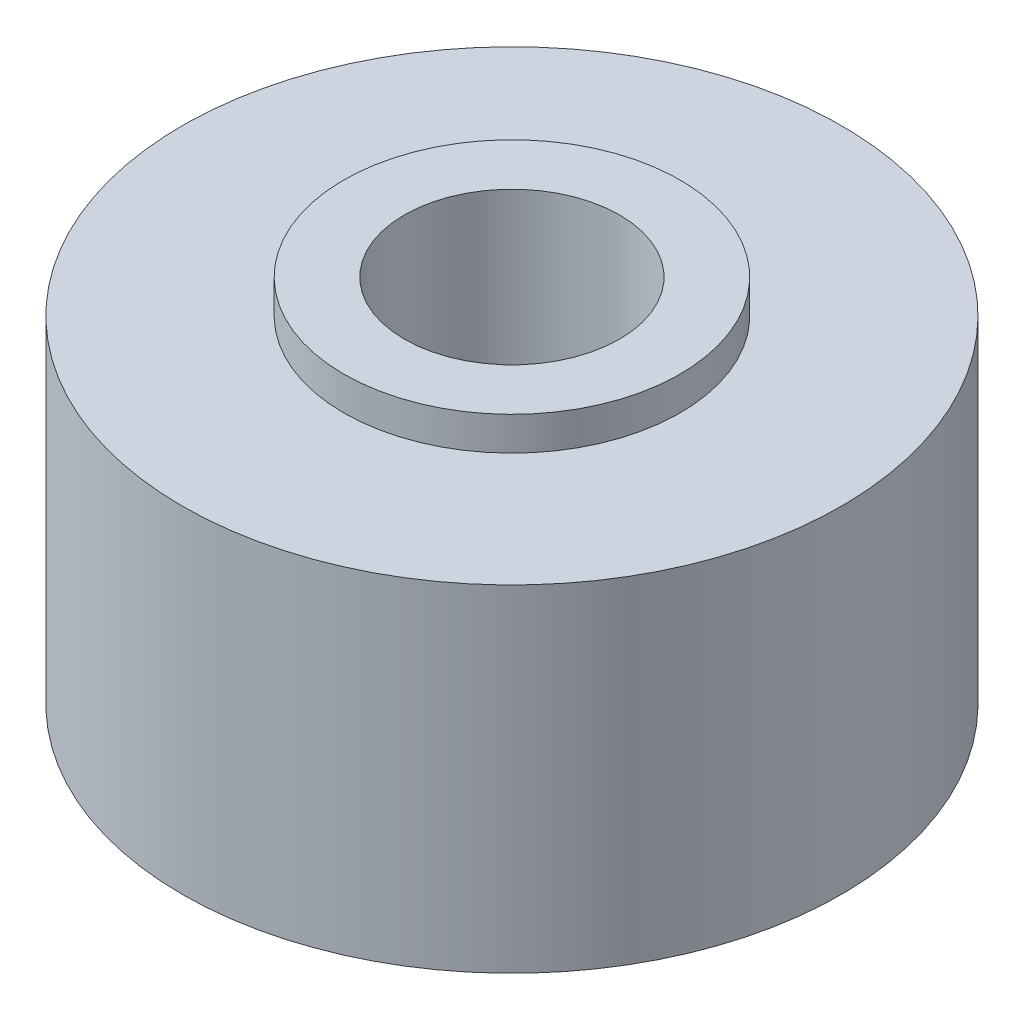
SolidWorks part; units mm, degrees
ref_plane "Front Plane" through (0, 0, 0) normal (0, 0, 1) x (1, 0, 0)
ref_plane "Top Plane" through (0, 0, 0) normal (0, 1, 0) x (1, 0, 0)
ref_plane "Right Plane" through (0, 0, 0) normal (1, 0, 0) x (0, 0, -1)
sketch "Sketch1" plane through (0, 0, 0) normal (0, 1, 0) x (1, 0, 0)
  circle A0 centre (0, 0) radius 4.9
  circle A1 centre (0, 0) radius 1.6
  dimension "D1" = 9.8
  dimension "D2" = 3.2
extrude "Boss-Extrude1" add sketch "Sketch1" along normal blind 5
sketch "Sketch2" plane through (0, 5, 0) normal (0, 1, 0) x (1, 0, 0)
  circle A0 centre (0, 0) radius 1.6
  circle A1 centre (0, 0) radius 2.5
extrude "Boss-Extrude2" add sketch "Sketch2" along normal blind 0.5
